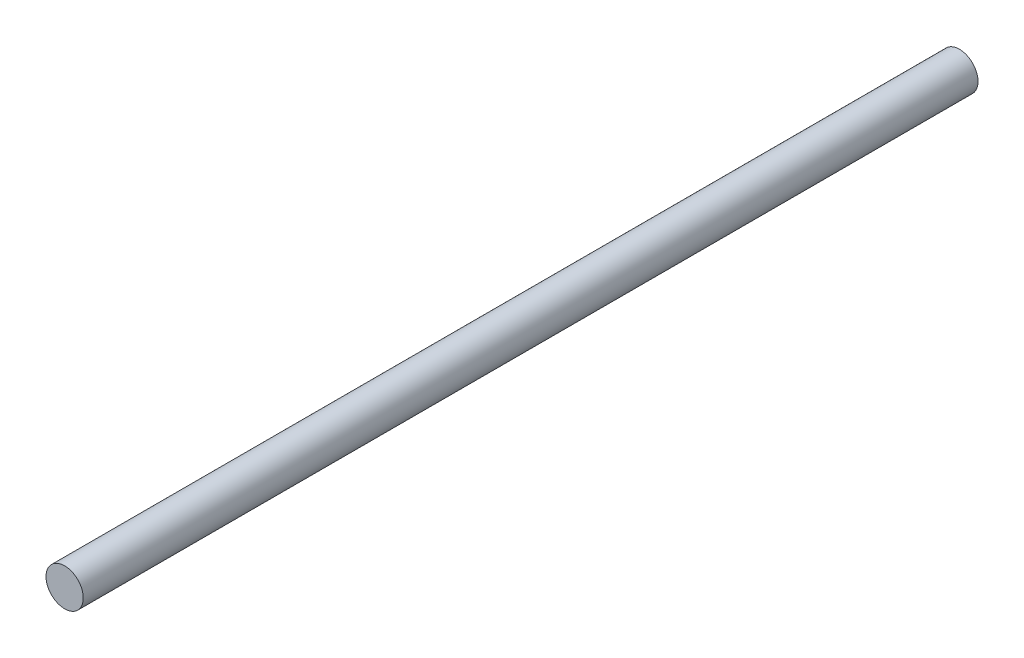
SolidWorks part; units mm, degrees
ref_plane "Front Plane" through (0, 0, 0) normal (0, 0, 1) x (1, 0, 0)
ref_plane "Top Plane" through (0, 0, 0) normal (0, 1, 0) x (1, 0, 0)
ref_plane "Right Plane" through (0, 0, 0) normal (1, 0, 0) x (0, 0, -1)
sketch "Sketch1" plane through (0, 0, 0) normal (0, 0, 1) x (1, 0, 0)
  circle A0 centre (0, 0) radius 3.175
extrude "Boss-Extrude1" add sketch "Sketch1" along normal blind 152.4
